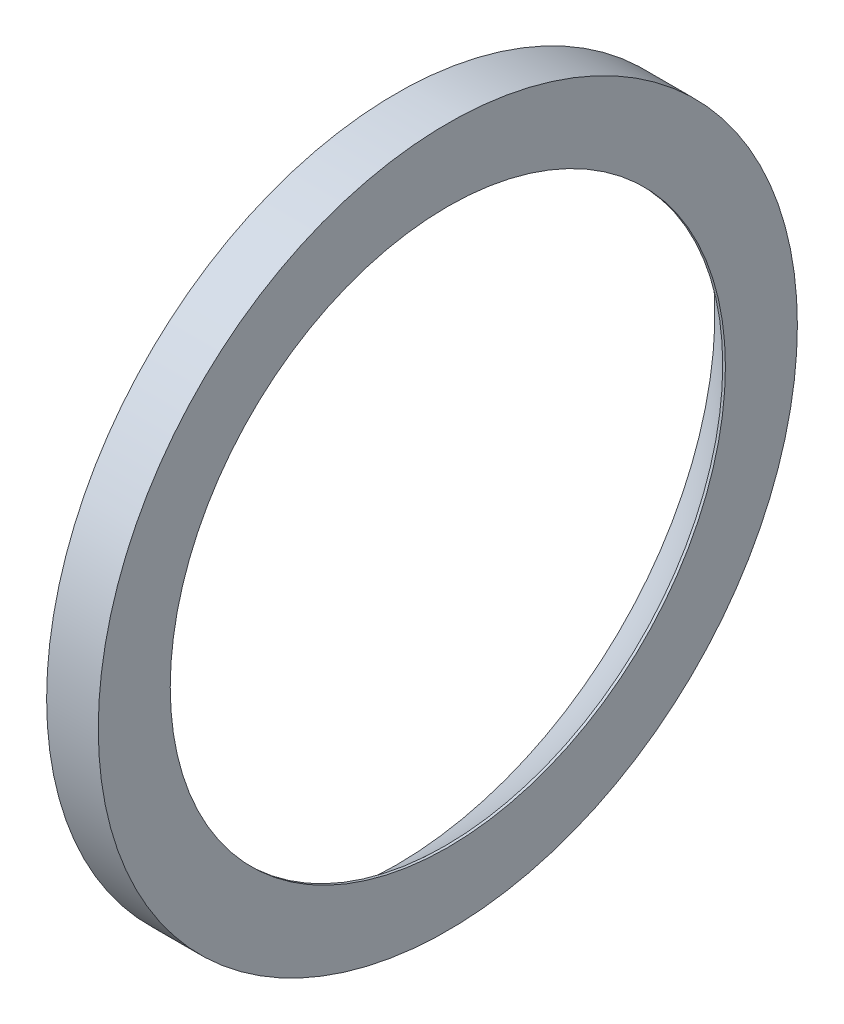
SolidWorks part; units mm, degrees
material "PTFE(ogólny)"
ref_plane "Przednia" through (0, 0, 0) normal (0, 0, 1) x (1, 0, 0)
ref_plane "Górna" through (0, 0, 0) normal (0, 1, 0) x (1, 0, 0)
ref_plane "Prawa" through (0, 0, 0) normal (1, 0, 0) x (0, 0, -1)
sketch "Szkic1" plane through (0, 0, 0) normal (0, 0, 1) x (1, 0, 0)
  line L2 (-18.7325, 0) -> (26.1216, 0) construction
  line L3 (13.3697, 13.5) -> (13.3697, 0) construction
  line L4 (10.9886, 15.5) -> (10.9886, 0) construction
  line L8 (0, 0) -> (12.0373, 14.7005) construction
  line L9 (10.9886, 15.5) -> (10.9886, 17)
  line L10 (10.9886, 17) -> (13.3697, 17)
  line L12 (13.3697, 17) -> (13.5, 17)
  line L13 (13.5, 17) -> (13.5, 13.5)
  line L14 (13.5, 13.5) -> (13.3697, 13.5)
  line L15 (13.5, 24.25) -> (13.5, -24.25) construction
  arc A1 (10.9886, 15.5) -> (13.3697, 13.5) centre (0, 0) cw
  dimension "D1" = 27
  dimension "D2" = 3.5
  dimension "D3" = 31
  dimension "D4" = 19
  dimension "D5" = 0
revolve "Obrót1" add sketch "Szkic1" angle 360 about L2
